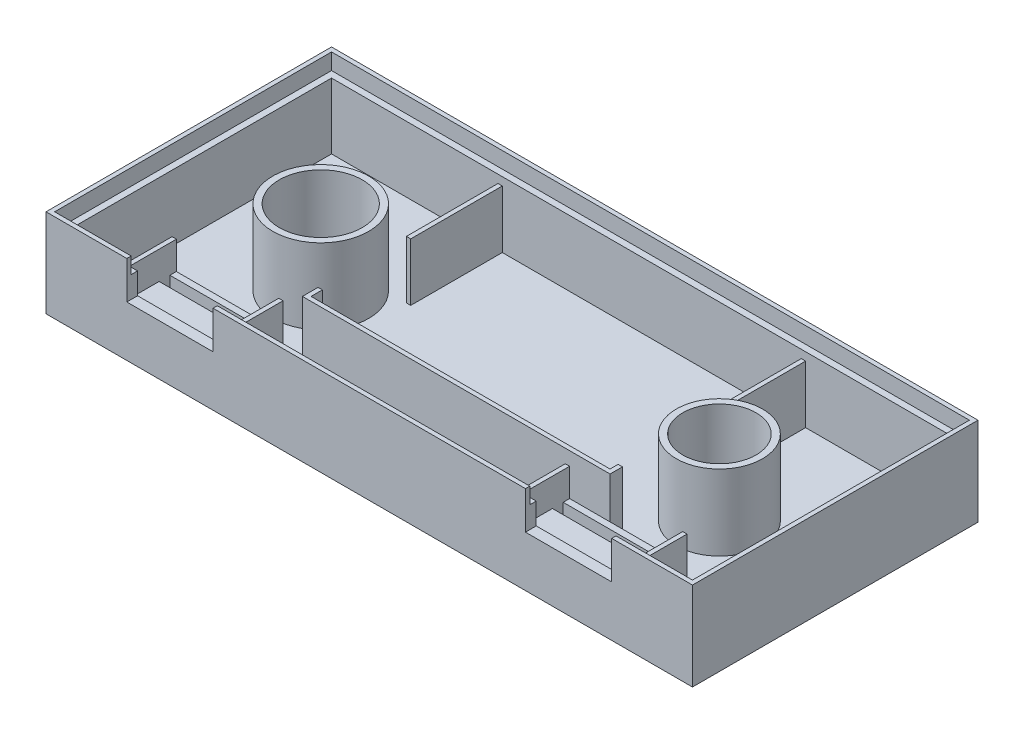
SolidWorks part; units mm, degrees
ref_plane "前视基准面" through (0, 0, 0) normal (0, 0, 1) x (1, 0, 0)
ref_plane "上视基准面" through (0, 0, 0) normal (0, 1, 0) x (1, 0, 0)
ref_plane "右视基准面" through (0, 0, 0) normal (1, 0, 0) x (0, 0, -1)
sketch "草图1" plane through (0, 0, 0) normal (0, 1, 0) x (1, 0, 0)
  line L1 (0, 0) -> (-120, 0)
  line L2 (0, 0) -> (0, 53)
  line L3 (0, 53) -> (-120, 53)
  line L4 (-120, 0) -> (-120, 53)
extrude "凸台-拉伸2" add sketch "草图1" along normal blind 16.4 contours L1 L4 L3 L2
sketch "草图4" plane through (0, 16.4, 0) normal (0, 1, 0) x (1, 0, 0)
  line L1 (-118, 51) -> (-2, 51)
  line L2 (-118, 51) -> (-118, 2)
  line L3 (-118, 2) -> (-2, 2)
  line L4 (-2, 51) -> (-2, 2)
extrude "切除-拉伸5" cut sketch "草图4" against normal blind 15.2
sketch3d "3D草图1" plane through (0, 0, 0) normal (0, 0, 1) x (1, 0, 0)
sketch "草图5" plane through (0, 16.4, 0) normal (0, 1, 0) x (1, 0, 0)
  line L1 (-0.8, 0.8) -> (-119.2, 0.8)
  line L2 (-0.8, 0.8) -> (-0.8, 52.2)
  line L3 (-0.8, 52.2) -> (-119.2, 52.2)
  line L4 (-119.2, 0.8) -> (-119.2, 52.2)
extrude "切除-拉伸6" cut sketch "草图5" against normal blind 3
sketch "草图6" plane through (0, 1.2, 0) normal (0, 1, 0) x (1, 0, 0)
  line L0 (-118, 51) -> (-2, 51) construction
  line L1 (-87.1, 51) -> (-30, 51)
  line L2 (-87.1, 51) -> (-87.1, 14.7)
  line L3 (-87.1, 14.7) -> (-30, 14.7)
  line L4 (-30, 51) -> (-30, 14.7)
extrude "凸台-拉伸3" add sketch "草图6" along normal blind 10.7
sketch "草图7" plane through (0, 11.9, 0) normal (0, 1, 0) x (1, 0, 0)
  line L0 (-30, 51) -> (-87.1, 51) construction
  line L1 (-86.3, 15.5) -> (-30.8, 15.5)
  line L2 (-86.3, 15.5) -> (-86.3, 51)
  line L3 (-86.3, 51) -> (-30.8, 51)
  line L4 (-30.8, 15.5) -> (-30.8, 51)
extrude "切除-拉伸7" cut sketch "草图7" against normal blind 10.7
sketch "草图8" plane through (0, 11.9, 0) normal (0, 1, 0) x (1, 0, 0)
  line L1 (-88.2288, 34) -> (-84.8278, 34)
  line L2 (-88.2288, 34) -> (-88.2288, 17.6)
  line L3 (-88.2288, 17.6) -> (-84.8278, 17.6)
  line L4 (-84.8278, 34) -> (-84.8278, 17.6)
extrude "切除-拉伸8" cut sketch "草图8" against normal blind 10.7
sketch "草图9" plane through (0, 1.2, 0) normal (0, 1, 0) x (1, 0, 0)
  circle A0 centre (-97, 28) radius 8.9
extrude "凸台-拉伸4" add sketch "草图9" along normal blind 14
sketch "草图10" plane through (0, 15.2, 0) normal (0, 1, 0) x (1, 0, 0)
  circle A0 centre (-97, 28) radius 7.7
extrude "切除-拉伸9" cut sketch "草图10" against normal blind 14
sketch "草图12" plane through (0, 11.9, 0) normal (0, 1, 0) x (1, 0, 0)
  line L0 (-30, 14.7) -> (-30, 51) construction
  line L1 (-31.4311, 37) -> (-30, 37)
  line L2 (-31.4311, 37) -> (-31.4311, 17)
  line L3 (-31.4311, 17) -> (-30, 17)
  line L4 (-30, 37) -> (-30, 17)
extrude "切除-拉伸10" cut sketch "草图12" against normal blind 10.7
sketch "草图11" plane through (0, 1.2, 0) normal (0, 1, 0) x (1, 0, 0)
  circle A0 centre (-23, 28) radius 8
extrude "凸台-拉伸8" add sketch "草图11" along normal blind 14 contours A0
sketch "草图13" plane through (0, 15.2, 0) normal (0, 1, 0) x (1, 0, 0)
  circle A0 centre (-23, 28) radius 6.8
extrude "切除-拉伸11" cut sketch "草图13" against normal blind 14
sketch "草图14" plane through (0, 1.2, 0) normal (0, 1, 0) x (1, 0, 0)
  line L0 (-2, 2) -> (-118, 2) construction
  line L1 (-34.3, 2) -> (-11.7, 2)
  line L2 (-34.3, 2) -> (-34.3, 10.7)
  line L3 (-34.3, 10.7) -> (-11.7, 10.7)
  line L4 (-11.7, 2) -> (-11.7, 10.7)
extrude "凸台-拉伸9" add sketch "草图14" along normal blind 12.2
sketch "草图15" plane through (0, 13.4, 0) normal (0, 1, 0) x (1, 0, 0)
  line L0 (-11.7, 2) -> (-2, 2) construction
  line L1 (-12.5, 2) -> (-33.5, 2)
  line L2 (-12.5, 2) -> (-12.5, 11.7504)
  line L3 (-12.5, 11.7504) -> (-33.5, 11.7504)
  line L4 (-33.5, 2) -> (-33.5, 11.7504)
extrude "切除-拉伸12" cut sketch "草图15" against normal blind 5.2
sketch "草图16" plane through (0, 16.4, 0) normal (0, 1, 0) x (1, 0, 0)
  line L0 (0, 0) -> (-120, 0) construction
  line L1 (-15, 0) -> (-31, 0)
  line L2 (-15, 0) -> (-15, 2)
  line L3 (-15, 2) -> (-31, 2)
  line L4 (-31, 0) -> (-31, 2)
  line L5 (-33.5, 2) -> (-12.5, 2) construction
extrude "切除-拉伸13" cut sketch "草图16" against normal blind 7
sketch "草图18" plane through (0, 8.2, 0) normal (0, 1, 0) x (1, 0, 0)
  line L0 (-12.5, 2) -> (-12.5, 10.7) construction
  line L1 (-12.5, 7.5) -> (-33.5, 7.5)
  line L2 (-12.5, 7.5) -> (-12.5, 9.5)
  line L3 (-12.5, 9.5) -> (-33.5, 9.5)
  line L4 (-33.5, 7.5) -> (-33.5, 9.5)
  line L5 (-33.5, 10.7) -> (-33.5, 2) construction
extrude "切除-拉伸14" cut sketch "草图18" against normal blind 7
sketch "草图19" plane through (0, 1.2, 0) normal (0, 1, 0) x (1, 0, 0)
  line L0 (-118, 2) -> (-34.3, 2) construction
  line L1 (-86.7, 2) -> (-107.3, 2)
  line L2 (-86.7, 2) -> (-86.7, 10.7)
  line L3 (-86.7, 10.7) -> (-107.3, 10.7)
  line L4 (-107.3, 2) -> (-107.3, 10.7)
extrude "凸台-拉伸10" add sketch "草图19" along normal blind 12.2
sketch "草图21" plane through (0, 13.4, 0) normal (0, 1, 0) x (1, 0, 0)
  line L0 (-86.7, 2) -> (-34.3, 2) construction
  line L1 (-87.5, 2) -> (-106.5, 2)
  line L2 (-87.5, 2) -> (-87.5, 11.5216)
  line L3 (-87.5, 11.5216) -> (-106.5, 11.5216)
  line L4 (-106.5, 2) -> (-106.5, 11.5216)
extrude "切除-拉伸15" cut sketch "草图21" against normal blind 5.2
sketch "草图23" plane through (0, 16.4, 0) normal (0, 1, 0) x (1, 0, 0)
  line L0 (-31, 0) -> (-120, 0) construction
  line L1 (-89, 0) -> (-105, 0)
  line L2 (-89, 0) -> (-89, 2)
  line L3 (-89, 2) -> (-105, 2)
  line L4 (-105, 0) -> (-105, 2)
  line L5 (-106.5, 2) -> (-87.5, 2) construction
extrude "切除-拉伸16" cut sketch "草图23" against normal blind 7
sketch "草图24" plane through (0, 8.2, 0) normal (0, 1, 0) x (1, 0, 0)
  line L0 (-106.5, 10.7) -> (-106.5, 2) construction
  line L1 (-106.5, 9.5) -> (-87.5, 9.5)
  line L2 (-106.5, 9.5) -> (-106.5, 7.5)
  line L3 (-106.5, 7.5) -> (-87.5, 7.5)
  line L4 (-87.5, 9.5) -> (-87.5, 7.5)
  line L5 (-87.5, 2) -> (-87.5, 10.7) construction
extrude "切除-拉伸17" cut sketch "草图24" against normal blind 7
sketch "草图25" plane through (0, 1.2, 0) normal (0, 1, 0) x (1, 0, 0)
  circle A0 centre (-7, 7) radius 1.2
extrude "切除-拉伸18" cut sketch "草图25" against normal blind 5
sketch "草图26" plane through (0, 1.2, 0) normal (0, 1, 0) x (1, 0, 0)
  circle A0 centre (-7, 46.4) radius 1.2
extrude "切除-拉伸19" cut sketch "草图26" against normal blind 5
sketch "草图27" plane through (0, 1.2, 0) normal (0, 1, 0) x (1, 0, 0)
  circle A0 centre (-112.7, 7) radius 1.2
extrude "切除-拉伸20" cut sketch "草图27" against normal blind 5
sketch "草图28" plane through (0, 1.2, 0) normal (0, 1, 0) x (1, 0, 0)
  circle A0 centre (-112.7, 46.4) radius 1.2
extrude "切除-拉伸21" cut sketch "草图28" against normal blind 5
